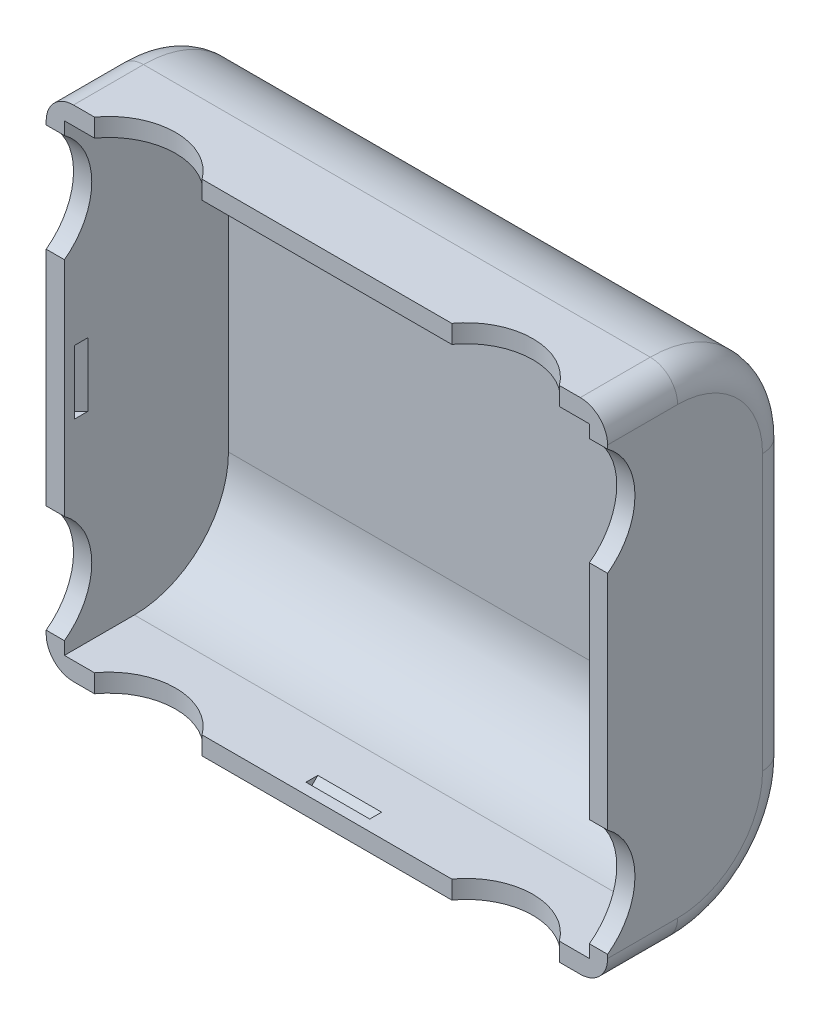
SolidWorks part; units mm, degrees
ref_plane "正面" through (0, 0, 0) normal (0, 0, 1) x (1, 0, 0)
ref_plane "平面" through (0, 0, 0) normal (0, 1, 0) x (1, 0, 0)
ref_plane "右側面" through (0, 0, 0) normal (1, 0, 0) x (0, 0, -1)
sketch "ｽｹｯﾁ2" plane through (0, 0, 0) normal (1, 0, 0) x (0, 0, -1)
  line L0 (-0.55, 17.7585) -> (-13.6693, 17.7585) construction
  line L1 (7.1258, 45.1585) -> (-0.55, 45.1585)
  line L2 (7.1258, -9.6415) -> (-0.55, -9.6415)
  line L3 (19.45, 32.8343) -> (19.45, 2.6827)
  line L6 (-0.55, 45.1585) -> (-0.55, -9.6415)
  arc A0 (7.1258, -9.6415) -> (19.45, 2.6827) centre (7.1258, 2.6827) ccw
  arc A1 (7.1258, 45.1585) -> (19.45, 32.8343) centre (7.1258, 32.8343) cw
  dimension "D1" = 54.8
  dimension "D2" = 20
extrude "ﾎﾞｽ - 押し出し1" add sketch "ｽｹｯﾁ2" along normal blind 61.6
shell "ｼｪﾙ1" thickness 2
ref_plane "平面1" through (30.8, 0, 0) normal (1, 0, 0) x (0, 0, -1)
ref_plane "平面2" through (0, 17.7585, 0) normal (0, 1, 0) x (1, 0, 0)
sketch "ｽｹｯﾁ11" plane through (0, 17.7585, 0) normal (0, 1, 0) x (1, 0, 0)
  line L0 (2.16, 2.1715) -> (1.2513, 1.2629)
  line L1 (1.2513, 1.2629) -> (1.2513, 0.5666)
  line L2 (1.2513, 0.5666) -> (2.16, 0.5666)
  line L3 (2.16, 2.1715) -> (2.16, 0.5666)
  line L4 (2, 1.7853) -> (1.4113, 1.1966) construction
  line L5 (1.4113, 1.1966) -> (1.4113, 0.7266) construction
  line L6 (1.4113, 0.7266) -> (2, 0.7266) construction
  line L7 (2, 7.1258) -> (2, -0.55) construction
  line L8 (2, 1.7853) -> (1.4113, 1.1966) construction
  line L9 (30.8, 19.45) -> (30.8, 7.1258) construction
  line L10 (1.4113, 1.1966) -> (1.4113, 0.7266) construction
  line L11 (1.4113, 0.7266) -> (2, 0.7266) construction
  line L12 (2, 1.7853) -> (2, 0.7266) construction
  line L17 (61.6, 19.45) -> (0, 19.45) construction
  line L18 (61.6, 7.1258) -> (0, 7.1258) construction
  line L19 (59.6, 1.7853) -> (59.6, 0.7266) construction
  line L20 (60.1887, 0.7266) -> (59.6, 0.7266) construction
  line L21 (60.1887, 1.1966) -> (60.1887, 0.7266) construction
  line L22 (59.6, 1.7853) -> (60.1887, 1.1966) construction
  line L23 (59.44, 2.1715) -> (59.44, 0.5666)
  line L24 (60.3487, 0.5666) -> (59.44, 0.5666)
  line L25 (60.3487, 1.2629) -> (60.3487, 0.5666)
  line L26 (59.44, 2.1715) -> (60.3487, 1.2629)
  dimension "D1" = 0.16
extrude "ｶｯﾄ - 押し出し8" cut sketch "ｽｹｯﾁ11" against normal mid plane 7
sketch "ｽｹｯﾁ12" plane through (61.6, 0, 0) normal (1, 0, 0) x (0, 0, -1)
  line L8 (-0.55, 41.7576) -> (-0.55, 42.1585)
  line L9 (-0.55, 5.5576) -> (-0.55, 29.9593)
  line L10 (-0.55, -6.6415) -> (-0.55, -6.2407)
  line L11 (-9.15, -6.6415) -> (-0.55, -6.6415)
  line L12 (-9.15, -6.2407) -> (-9.15, -6.6415)
  line L13 (-9.15, 29.9593) -> (-9.15, 5.5576)
  line L14 (-9.15, 42.1585) -> (-9.15, 41.7576)
  line L15 (-0.55, 42.1585) -> (-9.15, 42.1585)
  line L19 (-0.55, 41.7576) -> (-0.55, 29.9593)
  line L20 (-0.55, 5.5576) -> (-0.55, -6.2407)
  arc A4 (-0.55, 29.9593) -> (-0.55, 41.7576) centre (-4.85, 35.8585) ccw
  arc A5 (-0.55, -6.2407) -> (-0.55, 5.5576) centre (-4.85, -0.3415) ccw
  arc A6 (-9.15, 5.5576) -> (-9.15, -6.2407) centre (-4.85, -0.3415) ccw
  arc A7 (-9.15, 41.7576) -> (-9.15, 29.9593) centre (-4.85, 35.8585) ccw
  arc A8 (-0.55, 29.9593) -> (-0.55, 41.7576) centre (-4.85, 35.8585) ccw
  arc A9 (-0.55, -6.2407) -> (-0.55, 5.5576) centre (-4.85, -0.3415) ccw
  dimension "D1" = 0
extrude "ｶｯﾄ - 押し出し9" cut sketch "ｽｹｯﾁ12" against normal up to next
sketch "ｽｹｯﾁ13" plane through (0, 0, 0) normal (-1, 0, 0) x (0, 0, 1)
  line L1 (0.55, 29.9593) -> (0.55, 41.7576)
  line L2 (0.55, 29.9593) -> (0.55, 41.7576)
  line L3 (0.55, -6.2407) -> (0.55, 5.5576)
  line L4 (0.55, -6.2407) -> (0.55, 5.5576)
  arc A1 (0.55, 41.7576) -> (0.55, 29.9593) centre (4.85, 35.8585) ccw
  arc A2 (0.55, 41.7576) -> (0.55, 29.9593) centre (4.85, 35.8585) ccw
  arc A3 (0.55, 5.5576) -> (0.55, -6.2407) centre (4.85, -0.3415) ccw
  arc A4 (0.55, 5.5576) -> (0.55, -6.2407) centre (4.85, -0.3415) ccw
  dimension "D1" = 0
  dimension "D2" = 0
extrude "ｶｯﾄ - 押し出し10" cut sketch "ｽｹｯﾁ13" against normal up to next
sketch "ｽｹｯﾁ14" plane through (0, -9.6415, 0) normal (0, -1, 0) x (1, 0, 0)
  line L1 (5.3008, 0.55) -> (17.0992, 0.55)
  line L2 (44.5008, 0.55) -> (56.2992, 0.55)
  arc A0 (44.5008, 0.55) -> (56.2992, 0.55) centre (50.4, 4.85) ccw construction
  arc A2 (5.3008, 0.55) -> (17.0992, 0.55) centre (11.2, 4.85) ccw construction
  arc A4 (44.5008, 0.55) -> (56.2992, 0.55) centre (50.4, 4.85) ccw
  arc A6 (5.3008, 0.55) -> (17.0992, 0.55) centre (11.2, 4.85) ccw
extrude "ｶｯﾄ - 押し出し11" cut sketch "ｽｹｯﾁ14" against normal up to next
sketch "ｽｹｯﾁ15" plane through (0, 45.1585, 0) normal (0, 1, 0) x (1, 0, 0)
  line L1 (44.5008, -0.55) -> (56.2992, -0.55)
  line L2 (44.5008, -0.55) -> (56.2992, -0.55)
  line L3 (5.3008, -0.55) -> (17.0992, -0.55)
  line L4 (5.3008, -0.55) -> (17.0992, -0.55)
  arc A1 (56.2992, -0.55) -> (44.5008, -0.55) centre (50.4, -4.85) ccw
  arc A2 (56.2992, -0.55) -> (44.5008, -0.55) centre (50.4, -4.85) ccw
  arc A3 (17.0992, -0.55) -> (5.3008, -0.55) centre (11.2, -4.85) ccw
  arc A4 (17.0992, -0.55) -> (5.3008, -0.55) centre (11.2, -4.85) ccw
  dimension "D1" = 0
  dimension "D2" = 0
extrude "ｶｯﾄ - 押し出し12" cut sketch "ｽｹｯﾁ15" against normal up to next
sketch "ｽｹｯﾁ16" plane through (30.8, 0, 0) normal (1, 0, 0) x (0, 0, -1)
  line L0 (7.1258, 43.1585) -> (-0.55, 43.1585) construction
  line L1 (1.2213, -8.2302) -> (1.81, -7.6415) construction
  line L2 (0.7513, -8.2302) -> (1.2213, -8.2302) construction
  line L3 (0.7513, -7.6415) -> (0.7513, -8.2302) construction
  line L4 (1.81, -7.6415) -> (0.7513, -7.6415) construction
  line L5 (1.2213, -8.2302) -> (1.81, -7.6415) construction
  line L6 (0.7513, -8.2302) -> (1.2213, -8.2302) construction
  line L7 (0.7513, -7.6415) -> (0.7513, -8.2302) construction
  line L8 (2.0514, 43.0585) -> (0.6513, 43.0585)
  line L9 (0.6513, 43.0585) -> (0.6513, 43.8472)
  line L10 (0.6513, 43.8472) -> (1.2628, 43.8472)
  line L11 (1.2628, 43.8472) -> (2.0514, 43.0585)
  line L12 (-0.55, 17.7585) -> (19.45, 17.7585) construction
  line L13 (-0.55, 5.5576) -> (-0.55, 29.9593) construction
  line L14 (19.45, 2.6827) -> (19.45, 32.8343) construction
  line L15 (0.7513, -7.6415) -> (0.7513, -8.2302) construction
  line L16 (0.7513, -8.2302) -> (1.2213, -8.2302) construction
  line L17 (1.2213, -8.2302) -> (1.81, -7.6415) construction
  line L18 (1.81, -7.6415) -> (0.7513, -7.6415) construction
  line L19 (1.2628, -8.3302) -> (2.0514, -7.5415)
  line L20 (0.6513, -8.3302) -> (1.2628, -8.3302)
  line L21 (0.6513, -7.5415) -> (0.6513, -8.3302)
  line L22 (2.0514, -7.5415) -> (0.6513, -7.5415)
extrude "ｶｯﾄ - 押し出し13" cut sketch "ｽｹｯﾁ16" against normal mid plane 7
fillet "ﾌｨﾚｯﾄ1" radius 3 5 edges at (61.6, 45.1585, -3.2879) (61.6, 41.5488, -15.8403) (61.6, 17.7585, -19.45) (61.6, -6.0318, -15.8403) (61.6, -9.6415, -3.2879)
fillet "ﾌｨﾚｯﾄ2" radius 3 5 edges at (0, 45.1585, -3.2879) (0, 41.5488, -15.8403) (0, 17.7585, -19.45) (0, -6.0318, -15.8403) (0, -9.6415, -3.2879)
